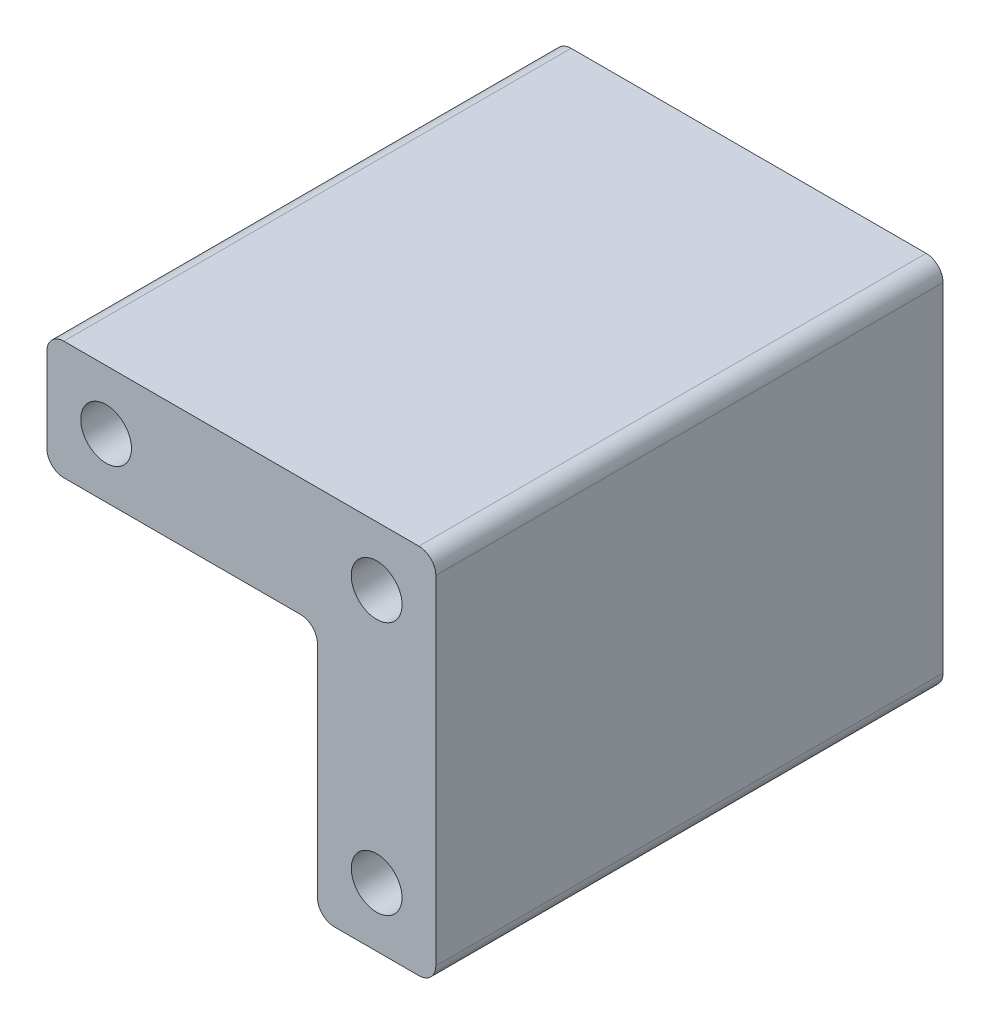
SolidWorks part; units mm, degrees
material "POM 乙缩醛共聚物"
ref_plane "前视基准面" through (0, 0, 0) normal (0, 0, 1) x (1, 0, 0)
ref_plane "上视基准面" through (0, 0, 0) normal (0, 1, 0) x (1, 0, 0)
ref_plane "右视基准面" through (0, 0, 0) normal (1, 0, 0) x (0, 0, -1)
sketch "草图1" plane through (0, 0, 0) normal (0, 0, 1) x (1, 0, 0)
  line L1 (-11.5, 11) -> (11.5, 11)
  line L2 (-11.5, 11) -> (-11.5, -11)
  line L3 (-11.5, -11) -> (11.5, -11)
  line L4 (11.5, 11) -> (11.5, -11)
  line L5 (-11.5, 11) -> (11.5, -11) construction
  line L6 (-11.5, -11) -> (11.5, 11) construction
  line L7 (-8, 7.5) -> (8, 7.5) construction
  line L8 (-8, 7.5) -> (-8, -7.5) construction
  line L9 (-8, -7.5) -> (8, -7.5) construction
  line L10 (8, 7.5) -> (8, -7.5) construction
  line L11 (-8, 7.5) -> (8, -7.5) construction
  line L12 (-8, -7.5) -> (8, 7.5) construction
  circle A0 centre (-8, 7.5) radius 1.5
  circle A1 centre (8, 7.5) radius 1.5
  circle A2 centre (-8, -7.5) radius 1.5
  circle A3 centre (8, -7.5) radius 1.5
  point P0 (0, 0)
  point P5 (0, 0)
  dimension "D5" = 3
  dimension "D6" = 3
  dimension "D7" = 3
  dimension "D8" = 3
  dimension "D1" = 22
  dimension "D2" = 23
  dimension "D3" = 15
  dimension "D4" = 16
extrude "凸台-拉伸1" add sketch "草图1" along normal blind 30
sketch "草图2" plane through (0, 0, 30) normal (0, 0, 1) x (1, 0, 0)
  line L1 (-11.5, -11) -> (4.5, -11)
  line L2 (-11.5, -11) -> (-11.5, 4)
  line L3 (-11.5, 4) -> (4.5, 4)
  line L4 (4.5, -11) -> (4.5, 4)
  circle A0 centre (8, -7.5) radius 1.5 construction
  circle A1 centre (-8, 7.5) radius 1.5 construction
  dimension "D1" = 3.5
  dimension "D2" = 3.5
extrude "切除-拉伸1" cut sketch "草图2" against normal through all
fillet "圆角1" radius 1 6 edges at (4.5, -11, 15) (11.5, -11, 15) (11.5, 11, 15) (-11.5, 11, 15) (4.5, 4, 15) (-11.5, 4, 15)
